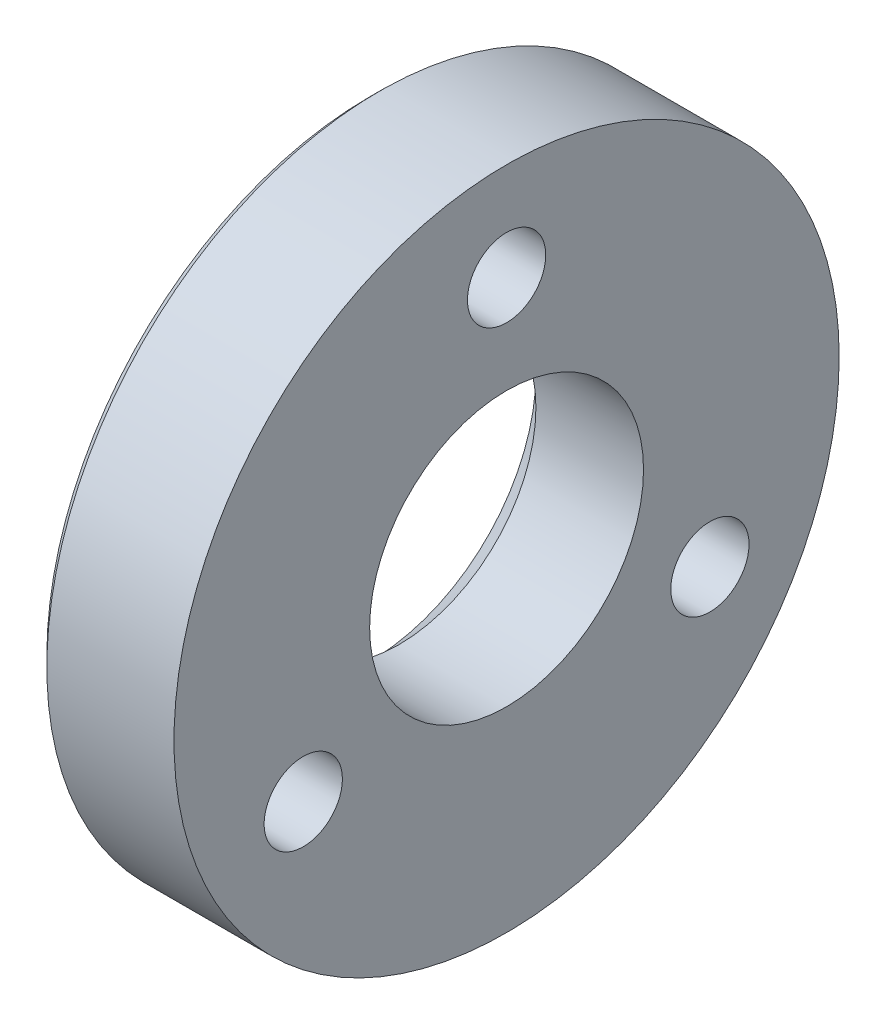
SolidWorks part; units mm, degrees
material "灰铸铁 HT150 (GB)"
ref_plane "前视基准面" through (0, 0, 0) normal (0, 0, 1) x (1, 0, 0)
ref_plane "上视基准面" through (0, 0, 0) normal (0, 1, 0) x (1, 0, 0)
ref_plane "右视基准面" through (0, 0, 0) normal (1, 0, 0) x (0, 0, -1)
sketch "草图1" plane through (0, 0, 0) normal (1, 0, 0) x (0, 0, -1)
  circle A0 centre (0, 0) radius 17
  circle A1 centre (0, 0) radius 7
  dimension "D1" = 34
  dimension "D2" = 14
extrude "凸台-拉伸1" add sketch "草图1" along normal blind 7
chamfer "倒角1" distance 0.5 angle 45 1 edges at (0, 0, -17)
chamfer "倒角2" distance 1.5 angle 45 1 edges at (0, 0, -7)
sketch "草图2" plane through (0, 0, 0) normal (1, 0, 0) x (0, 0, -1)
  line L0 (0, 0) -> (0, 12)
  circle A0 centre (0, 0) radius 12 construction
  circle A1 centre (0, 12) radius 2
  circle A2 centre (10.3923, -6) radius 2
  circle A3 centre (-10.3923, -6) radius 2
  dimension "D1" = 24
  dimension "D2" = 4
  dimension "D3" = 3
extrude "切除-拉伸1" cut sketch "草图2" against normal through all both and the other way through all
sketch "草图3" plane through (0, 0, 0) normal (-1, 0, 0) x (0, 0, 1)
  circle A0 centre (0, 12) radius 3
  dimension "D1" = 6
extrude "切除-拉伸2" cut sketch "草图3" against normal blind 3 and the other way through all
pattern_circular "阵列(圆周)1" count 3 every 120 about axis through (0, 0, 0) along (1, 0, 0) of "切除-拉伸2"
